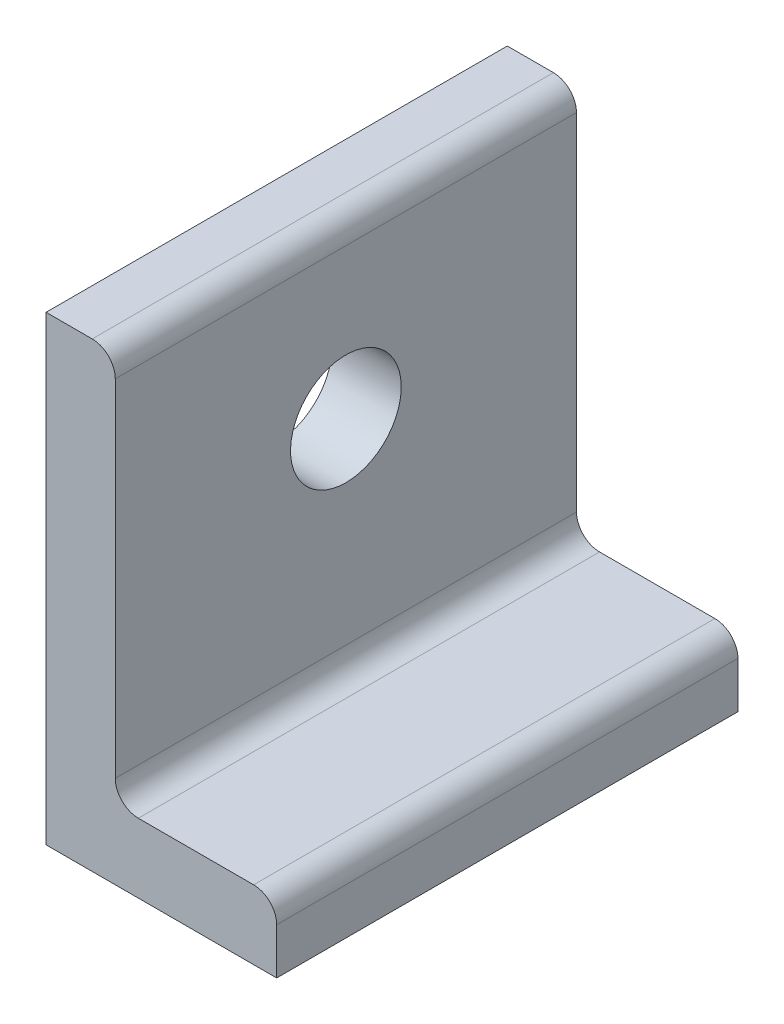
SolidWorks part; units mm, degrees
ref_plane "前视基准面" through (0, 0, 0) normal (0, 0, 1) x (1, 0, 0)
ref_plane "上视基准面" through (0, 0, 0) normal (0, 1, 0) x (1, 0, 0)
ref_plane "右视基准面" through (0, 0, 0) normal (1, 0, 0) x (0, 0, -1)
other "Configuration Table"
sketch "草图1" plane through (0, 0, 0) normal (0, 0, 1) x (1, 0, 0)
  line L0 (0, 20) -> (0, 0)
  line L1 (0, 0) -> (10, 0)
  line L2 (10, 0) -> (10, 3)
  line L3 (10, 3) -> (3, 3)
  line L4 (3, 3) -> (3, 20)
  line L5 (3, 20) -> (0, 20)
  dimension "D1" = 3
  dimension "D2" = 3
  dimension "D3" = 10
  dimension "D4" = 20
extrude "凸台-拉伸1" add sketch "草图1" along normal blind 20
sketch "草图2" plane through (0, 0, 0) normal (-1, 0, 0) x (0, 0, 1)
  line L0 (10, 25.0412) -> (10, -4.6271) construction
  line L1 (20, 20) -> (20, 0) construction
  line L2 (0, 20) -> (0, 0) construction
  line L3 (20, 0) -> (0, 0) construction
  circle A0 centre (10, 12.5) radius 2.4
  dimension "D1" = 4.8
  dimension "D2" = 12.5
extrude "切除-拉伸1" cut sketch "草图2" against normal blind 15
fillet "圆角1" radius 1 3 edges at (10, 3, 10) (3, 20, 10) (3, 3, 10)
